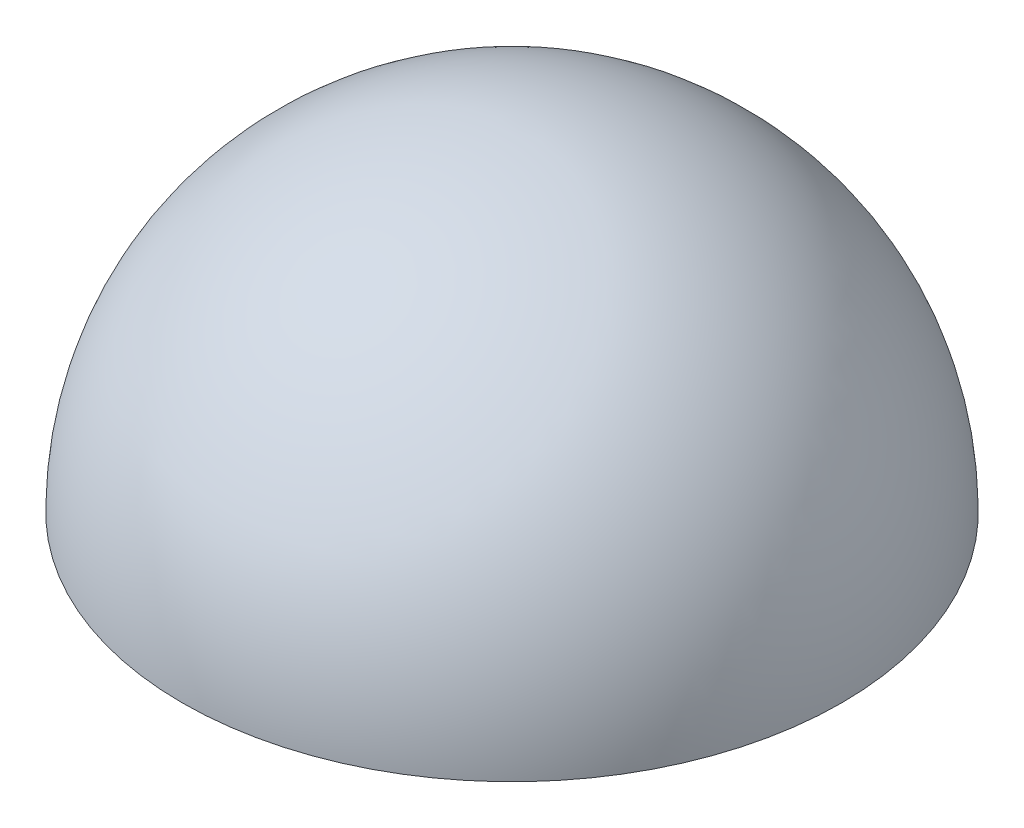
SolidWorks part; units mm, degrees
ref_plane "Front Plane" through (0, 0, 0) normal (0, 0, 1) x (1, 0, 0)
ref_plane "Top Plane" through (0, 0, 0) normal (0, 1, 0) x (1, 0, 0)
ref_plane "Right Plane" through (0, 0, 0) normal (1, 0, 0) x (0, 0, -1)
sketch "Sketch1" plane through (0, 0, 0) normal (0, 0, 1) x (1, 0, 0)
  line L0 (25.4, 0) -> (22.86, 0)
  line L2 (0, 22.86) -> (0, 25.4)
  arc A0 (25.4, 0) -> (0, 25.4) centre (0, 0) ccw
  arc A1 (22.86, 0) -> (0, 22.86) centre (0, 0) ccw
ref_axis "Axis2" through (0, 26.67, 0) along (0, -1, 0)
revolve "Revolve3" add sketch "Sketch1" angle 360 about axis through (0, 26.67, 0) along (0, -1, 0)
